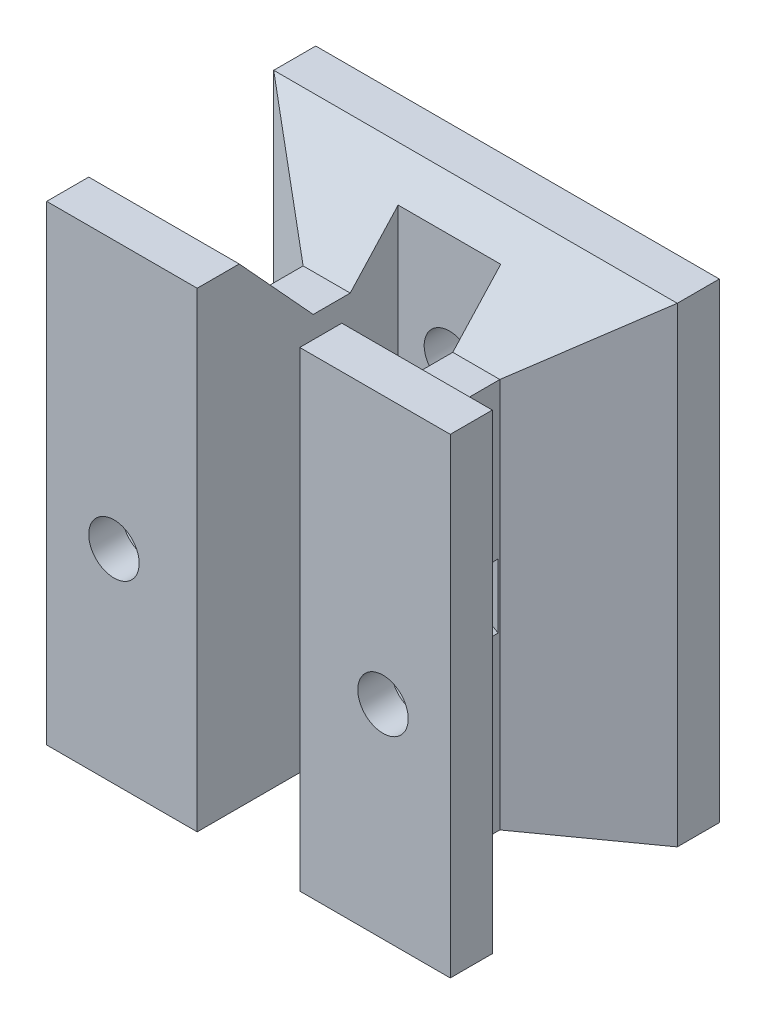
SolidWorks part; units mm, degrees
ref_plane "Plano frontal" through (0, 0, 0) normal (0, 0, 1) x (1, 0, 0)
ref_plane "Plano superior" through (0, 0, 0) normal (0, 1, 0) x (1, 0, 0)
ref_plane "Plano direito" through (0, 0, 0) normal (1, 0, 0) x (0, 0, -1)
sketch "Esboço1" plane through (0, 0, 0) normal (0, 0, 1) x (1, 0, 0)
  line L0 (12, 28) -> (12, 0) construction
  line L1 (0, 0) -> (24, 0)
  line L2 (0, 0) -> (0, 28)
  line L3 (0, 28) -> (24, 28)
  line L4 (24, 0) -> (24, 28)
  line L5 (0, 14) -> (24, 14) construction
  circle A0 centre (12, 19.85) radius 1.5
  circle A1 centre (12, 8.15) radius 1.5
  point P13 (12, 9.65)
  point P14 (12, 18.35)
  dimension "D3" = 3
  dimension "D1" = 24
  dimension "D2" = 28
  dimension "D4" = 8.7
extrude "Ressalto-extrusão1" add sketch "Esboço1" along normal blind 16
sketch "Esboço2" plane through (0, 0, 0) normal (0, 1, 0) x (1, 0, 0)
  line L0 (12, 0) -> (12, -16) construction
  line L1 (24, 0) -> (0, 0) construction
  line L2 (24, -16) -> (0, -16) construction
  line L3 (8.95, -16) -> (8.95, -4.05)
  line L4 (8.95, -4.05) -> (15.05, -4.05)
  line L5 (15.05, -4.05) -> (15.05, -16)
  line L6 (0, -13.5) -> (6.15, -9.1)
  line L7 (0, -16) -> (0, 0) construction
  line L8 (6.15, -9.1) -> (6.15, -6.9)
  line L9 (6.15, -6.9) -> (0, -2.5)
  line L10 (17.85, -6.9) -> (24, -2.5)
  line L11 (17.85, -9.1) -> (17.85, -6.9)
  line L12 (24, -13.5) -> (17.85, -9.1)
  line L13 (8.95, -16) -> (15.05, -16)
  line L14 (24, -13.5) -> (24, -2.5)
  line L15 (0, -2.5) -> (0, -13.5)
  dimension "D1" = 4.05
  dimension "D2" = 6.1
  dimension "D3" = 2.5
  dimension "D4" = 2.5
  dimension "D5" = 2.8
  dimension "D6" = 2.2
extrude "Corte-extrusão1" cut sketch "Esboço2" along normal through all
sketch "Esboço3" plane through (0, 0, 0) normal (1, 0, 0) x (0, 0, -1)
  line L0 (-8, 0) -> (-8, 28) construction
  line L1 (-9.1, 0) -> (-6.9, 0) construction
  line L2 (-9.1, 28) -> (-6.9, 28) construction
  line L3 (-13.5, 28) -> (-9.1, 23.2)
  line L4 (-9.1, 28) -> (-9.1, 0) construction
  line L5 (-9.1, 23.2) -> (-6.9, 23.2)
  line L6 (-2.5, 28) -> (-6.9, 23.2)
  line L7 (-2.5, 28) -> (-13.5, 28)
  point P13 (-8, 23.2)
  dimension "D1" = 23.2
extrude "Corte-extrusão3" cut sketch "Esboço3" along normal through all
sketch "Esboço4" plane through (0, 0, 16) normal (0, 0, 1) x (1, 0, 0)
  line L0 (12, 28) -> (12, 0) construction
  line L1 (24, 28) -> (0, 28) construction
  line L2 (15.05, 0) -> (8.95, 0) construction
  line L4 (8.95, 28) -> (0, 28) construction
  circle A0 centre (4, 12.1) radius 1.5
  circle A1 centre (20, 12.1) radius 1.5
  point P12 (5.5, 12.1)
  point P13 (18.5, 12.1)
  point P15 (4, 13.6)
  dimension "D3" = 3
  dimension "D1" = 14.4
  dimension "D2" = 13
extrude "Corte-extrusão4" cut sketch "Esboço4" against normal blind 7
sketch "Esboço5" plane through (0, 0, 16) normal (0, 0, 1) x (1, 0, 0)
  line L1 (4, 8.95) -> (6.728, 10.525)
  line L2 (6.728, 10.525) -> (6.728, 13.675)
  line L3 (6.728, 13.675) -> (4, 15.25)
  line L4 (4, 15.25) -> (1.272, 13.675)
  line L5 (1.272, 13.675) -> (1.272, 10.525)
  line L6 (1.272, 10.525) -> (4, 8.95)
  line L7 (20, 8.95) -> (22.728, 10.525)
  line L8 (22.728, 10.525) -> (22.728, 13.675)
  line L9 (22.728, 13.675) -> (20, 15.25)
  line L10 (20, 15.25) -> (17.272, 13.675)
  line L11 (17.272, 13.675) -> (17.272, 10.525)
  line L12 (17.272, 10.525) -> (20, 8.95)
  circle A0 centre (4, 12.1) radius 2.728 construction
  circle A1 centre (20, 12.1) radius 2.728 construction
  point P10 (20, 9.5271)
  dimension "D1" = 6.3
extrude "Corte-extrusão5" cut sketch "Esboço5" against normal blind 9
sketch "Esboço6" plane through (0, 0, 16) normal (0, 0, 1) x (1, 0, 0)
  line L0 (12, 28) -> (12, 0) construction
  line L1 (24, 28) -> (0, 28) construction
  line L2 (15.05, 0) -> (8.95, 0) construction
  line L3 (4, 15.25) -> (4, 8.95) construction
  line L4 (4, 8.95) -> (6.728, 10.525) construction
  line L5 (1.272, 10.525) -> (4, 8.95) construction
  line L6 (6.728, 10.525) -> (4, 8.95)
  line L7 (4, 8.95) -> (6.728, 10.525)
  line L8 (6.728, 10.525) -> (6.728, 13.675)
  line L9 (6.728, 13.675) -> (4, 15.25)
  line L10 (4, 15.25) -> (1.272, 13.675)
  line L11 (1.272, 13.675) -> (1.272, 10.525)
  line L12 (1.272, 10.525) -> (4, 8.95)
  line L13 (6.728, 13.675) -> (6.728, 10.525)
  line L14 (4, 15.25) -> (6.728, 13.675)
  line L15 (1.272, 13.675) -> (4, 15.25)
  line L16 (1.272, 10.525) -> (1.272, 13.675)
  line L17 (4, 8.95) -> (1.272, 10.525)
  line L18 (4, 8.95) -> (6.728, 10.525)
  line L19 (6.728, 10.525) -> (6.728, 13.675)
  line L20 (6.728, 13.675) -> (4, 15.25)
  line L21 (4, 15.25) -> (1.272, 13.675)
  line L22 (1.272, 13.675) -> (1.272, 10.525)
  line L23 (6.728, 10.525) -> (4, 8.95)
  line L24 (6.728, 13.675) -> (6.728, 10.525)
  line L25 (4, 15.25) -> (6.728, 13.675)
  line L26 (1.272, 13.675) -> (4, 15.25)
  line L27 (1.272, 10.525) -> (1.272, 13.675)
  line L28 (4, 8.95) -> (1.272, 10.525)
  line L29 (1.272, 10.525) -> (4, 8.95)
  line L30 (20, 15.25) -> (20, 8.95) construction
  line L31 (22.728, 10.525) -> (20, 8.95)
  line L32 (20, 8.95) -> (22.728, 10.525)
  line L33 (22.728, 10.525) -> (22.728, 13.675)
  line L34 (22.728, 13.675) -> (20, 15.25)
  line L35 (20, 15.25) -> (17.272, 13.675)
  line L36 (17.272, 13.675) -> (17.272, 10.525)
  line L37 (17.272, 10.525) -> (20, 8.95)
  line L38 (22.728, 13.675) -> (22.728, 10.525)
  line L39 (20, 15.25) -> (22.728, 13.675)
  line L40 (17.272, 13.675) -> (20, 15.25)
  line L41 (17.272, 10.525) -> (17.272, 13.675)
  line L42 (20, 8.95) -> (17.272, 10.525)
  line L43 (20, 8.95) -> (22.728, 10.525)
  line L44 (22.728, 10.525) -> (22.728, 13.675)
  line L45 (22.728, 13.675) -> (20, 15.25)
  line L46 (20, 15.25) -> (17.272, 13.675)
  line L47 (17.272, 13.675) -> (17.272, 10.525)
  line L48 (22.728, 10.525) -> (20, 8.95)
  line L49 (22.728, 13.675) -> (22.728, 10.525)
  line L50 (20, 15.25) -> (22.728, 13.675)
  line L51 (17.272, 13.675) -> (20, 15.25)
  line L52 (17.272, 10.525) -> (17.272, 13.675)
  line L53 (20, 8.95) -> (17.272, 10.525)
  line L54 (17.272, 10.525) -> (20, 8.95)
  circle A0 centre (4, 12.1) radius 2.728 construction
  circle A1 centre (4, 12.1) radius 1.5
  circle A2 centre (20, 12.1) radius 2.728 construction
  circle A3 centre (20, 12.1) radius 1.5
  line M2 (6.728, 10.525) -> (4, 8.95)
  line M3 (4, 8.95) -> (1.272, 10.525)
  line M4 (1.272, 10.525) -> (1.272, 13.675)
  line M5 (1.272, 13.675) -> (4, 15.25)
  line M6 (4, 15.25) -> (6.728, 13.675)
  line M7 (6.728, 13.675) -> (6.728, 10.525)
  dimension "D1" = 3
extrude "Ressalto-extrusão2" add sketch "Esboço6" against normal blind 2 contours A1 M2 M7 M6 M5 M4 M3 | L36 L37 L31 L33 L34 L35 A3
